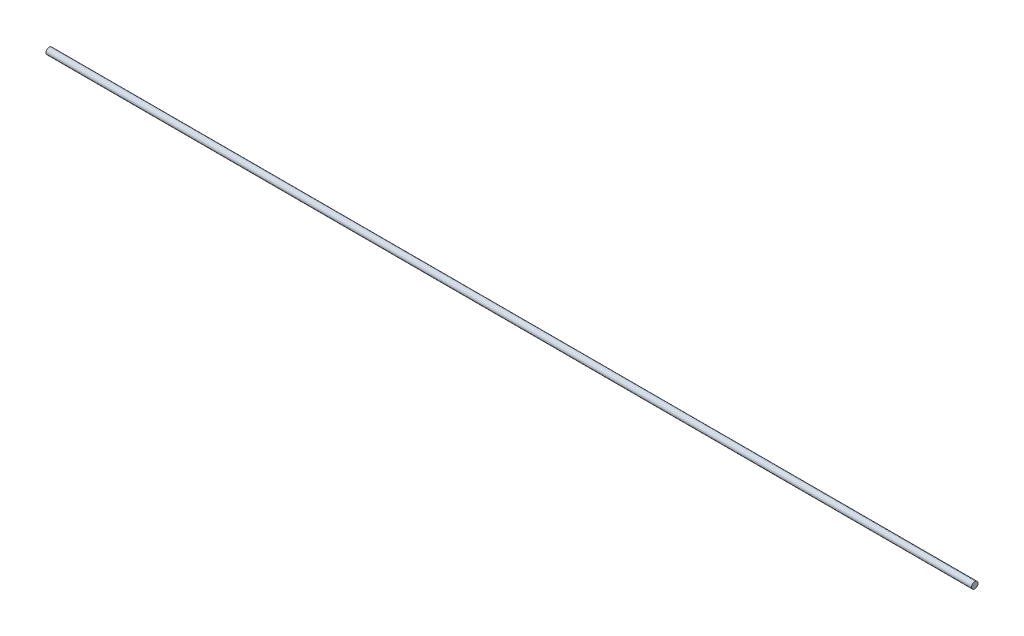
SolidWorks part; units mm, degrees
material "Hexcel AS4C (3000 丝)"
ref_plane "前视基准面" through (0, 0, 0) normal (0, 0, 1) x (1, 0, 0)
ref_plane "上视基准面" through (0, 0, 0) normal (0, 1, 0) x (1, 0, 0)
ref_plane "右视基准面" through (0, 0, 0) normal (1, 0, 0) x (0, 0, -1)
sketch "草图1" plane through (0, 0, 0) normal (1, 0, 0) x (0, 0, -1)
  circle A0 centre (0, 0) radius 0.5
  dimension "D1" = 1
extrude "凸台-拉伸1" add sketch "草图1" along normal blind 145
sketch "草图2" plane through (145, 0, 0) normal (1, 0, 0) x (0, 0, -1)
  point P0 (0, 0)
